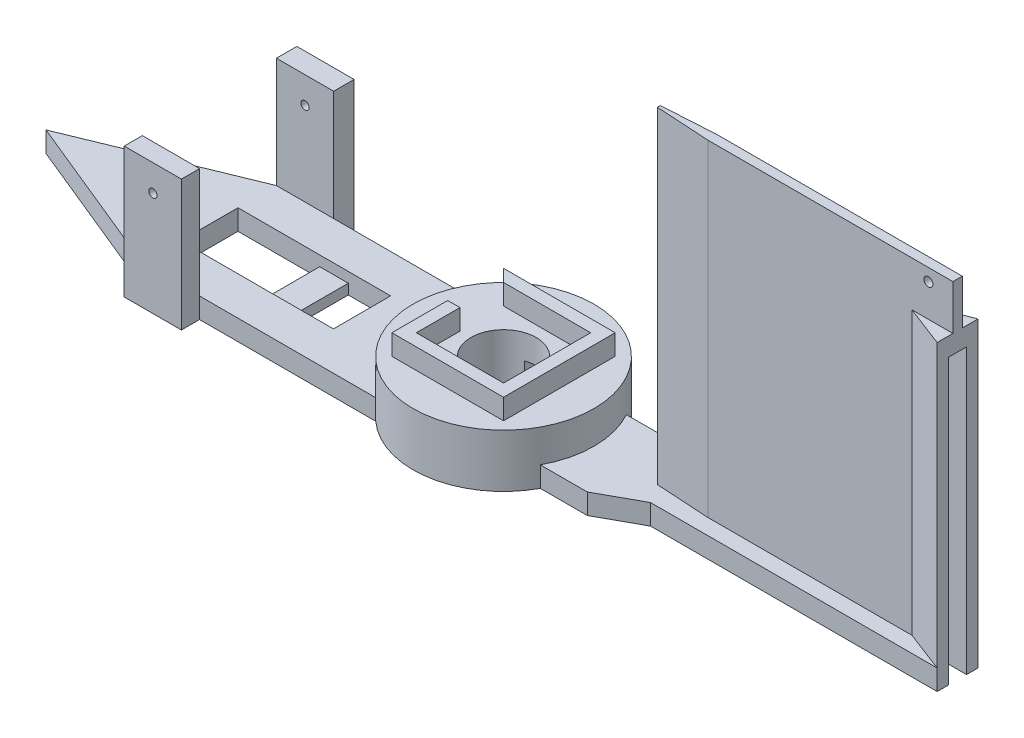
SolidWorks part; units mm, degrees
ref_plane "Front Plane" through (0, 0, 0) normal (0, 0, 1) x (1, 0, 0)
ref_plane "Top Plane" through (0, 0, 0) normal (0, 1, 0) x (1, 0, 0)
ref_plane "Right Plane" through (0, 0, 0) normal (1, 0, 0) x (0, 0, -1)
sketch "Sketch1" plane through (0, 0, 0) normal (0, 1, 0) x (1, 0, 0)
  circle A0 centre (0, 0) radius 16.15
  circle A1 centre (0, 0) radius 22.15
  dimension "D1" = 32.3
  dimension "D2" = 44.3
extrude "Boss-Extrude1" add sketch "Sketch1" along normal blind 10
sketch "Sketch2" plane through (0, 10, 0) normal (0, 1, 0) x (1, 0, 0)
  circle A0 centre (0, 0) radius 22.15
  circle A1 centre (0, 0) radius 12.15
  dimension "D1" = 24.3
extrude "Boss-Extrude2" add sketch "Sketch2" along normal blind 3
sketch "Sketch3" plane through (0, 13, 0) normal (0, 1, 0) x (1, 0, 0)
  line L0 (0, 0) -> (-65, 0)
  line L1 (-65, 0) -> (-65, -16.41)
  line L2 (-65, 0) -> (-65, 16.41)
  line L3 (-65, -16.41) -> (0, -16.41)
  line L4 (0, -16.41) -> (0, 0)
  line L5 (-65, 16.41) -> (0, 16.41)
  line L6 (0, 16.41) -> (0, 0)
  circle A0 centre (0, 0) radius 22.15
  circle M4 centre (0, 0) radius 22.15
  dimension "D1" = 65
  dimension "D2" = 16.41
extrude "Boss-Extrude3" add sketch "Sketch3" against normal up to surface (5 mm away) from offset 8 contours L5 L2 L0 M4 | L1 L3 L0 M4 up to face at (0, 0, 22.15) offset against normal yes
sketch "Sketch10" plane through (0, 5, 0) normal (0, 1, 0) x (1, 0, 0)
  line L1 (-65, -16.41) -> (-58, -16.41)
  line L2 (-65, -16.41) -> (-65, -20.8481)
  line L3 (-65, -20.8481) -> (-58, -20.8481)
  line L4 (-58, -16.41) -> (-58, -20.8481)
  line L5 (-65, -16.41) -> (-72, -16.41)
  line L6 (-65, -16.41) -> (-65, -20.8481)
  line L7 (-65, -20.8481) -> (-72, -20.8481)
  line L8 (-72, -16.41) -> (-72, -20.8481)
  line L9 (-65, 16.41) -> (-58, 16.41)
  line L10 (-65, 16.41) -> (-65, 21.41)
  line L11 (-65, 21.41) -> (-58, 21.41)
  line L12 (-58, 16.41) -> (-58, 21.41)
  line L13 (-65, 16.41) -> (-72, 16.41)
  line L14 (-65, 16.41) -> (-65, 21.41)
  line L15 (-65, 21.41) -> (-72, 21.41)
  line L16 (-72, 16.41) -> (-72, 21.41)
  line M6 (-14.8773, 16.41) -> (-65, 16.41)
  line M8 (-65, -16.41) -> (-14.8773, -16.41)
  dimension "D1" = 7
  dimension "D2" = 5
extrude "Boss-Extrude5" add sketch "Sketch10" along normal blind 27 separate body contours L5 L8 L7 L2 | L4 L2 L3 M8 | L16 L13 L10 L15 | L12 L11 L10 M6
sketch "Sketch11" plane through (0, 0, 20.8481) normal (0, 0, 1) x (1, 0, 0)
  line L0 (-65, 32) -> (-65, 25.5)
  line L1 (-58, 32) -> (-72, 32) construction
  circle A0 centre (-65, 25.5) radius 1
  dimension "D2" = 2
  dimension "D1" = 6.5
extrude "Cut-Extrude2" cut sketch "Sketch11" against normal through all
sketch "Sketch12" plane through (0, 0, 0) normal (0, -1, 0) x (1, 0, 0)
  line L1 (-72, 20.8481) -> (-58, 20.8481)
  line L2 (-72, 20.8481) -> (-72, -21.41)
  line L3 (-72, -21.41) -> (-58, -21.41)
  line L4 (-58, 20.8481) -> (-58, -21.41)
extrude "Boss-Extrude6" add sketch "Sketch12" against normal up to surface (5 mm away) up to face at (-65, 5, 18.6291)
sketch "Sketch13" plane through (0, 0, 0) normal (0, -1, 0) x (1, 0, 0)
  line L1 (16.15, 0) -> (111.15, 0)
  line L2 (16.15, 0) -> (16.15, 5)
  line L3 (16.15, 5) -> (111.15, 5)
  line L4 (111.15, 0) -> (111.15, 5)
  line L5 (16.15, 0) -> (111.15, 0)
  line L6 (16.15, 0) -> (16.15, -5)
  line L7 (16.15, -5) -> (111.15, -5)
  line L8 (111.15, 0) -> (111.15, -5)
  circle A0 centre (0, 0) radius 16.15 construction
  circle A1 centre (0, 0) radius 16.15 construction
  arc M11 (-14.8773, -16.41) -> (-14.8773, 16.41) centre (0, 0) ccw
  dimension "D1" = 5
  dimension "D2" = 95
extrude "Boss-Extrude7" add sketch "Sketch13" against normal blind 5 contours L8 L1 L7 M11 | L1 L4 L3 M11
sketch "Sketch14" plane through (0, 5, 0) normal (0, 1, 0) x (1, 0, 0)
  line L0 (22.15, 0) -> (32.15, 0)
  line L1 (111.15, 0) -> (111.15, 1.15)
  line L2 (111.15, -5) -> (111.15, 5) construction
  line L3 (111.15, 0) -> (111.15, -1.15)
  line L6 (111.15, 1.15) -> (51.15, 1.15)
  line L7 (111.15, -1.15) -> (51.15, -1.15)
  line L8 (32.15, 0) -> (51.15, 1.15)
  line L9 (51.15, -1.15) -> (32.15, 0)
  arc A0 (21.5783, -5) -> (21.5783, 5) centre (0, 0) ccw construction
  dimension "D1" = 10
  dimension "D2" = 1.15
  dimension "D3" = 60
extrude "Boss-Extrude8" add sketch "Sketch14" along normal blind 80
sketch "Sketch16" plane through (0, 13, 0) normal (0, 1, 0) x (1, 0, 0)
  line L0 (0, 0) -> (0, -10.64)
  line L1 (0, -10.64) -> (-10.64, -10.64)
  line L2 (-10.64, -10.64) -> (-10.64, -13.14)
  line L3 (-10.64, -10.64) -> (10.7, -10.64)
  line L4 (-10.64, -10.64) -> (-10.64, 10.7)
  line L5 (-10.64, 10.7) -> (10.7, 10.7)
  line L6 (10.7, -10.64) -> (10.7, 10.7)
  line L7 (-10.64, -13.14) -> (-13.14, -13.14)
  line L9 (-13.14, -13.14) -> (13.2, -13.14)
  line L10 (-13.14, -13.14) -> (-13.14, 13.2)
  line L11 (-13.14, 13.2) -> (13.2, 13.2)
  line L12 (13.2, -13.14) -> (13.2, 13.2)
  dimension "D1" = 10.64
  dimension "D2" = 21.34
  dimension "D3" = 2.5
  dimension "D4" = 26.34
extrude "Boss-Extrude9" add sketch "Sketch16" along normal blind 6
sketch "Sketch17" plane through (0, 19, 0) normal (0, 1, 0) x (1, 0, 0)
  line L0 (-13.14, -13.14) -> (-13.14, 13.2) construction
  line L1 (-13.14, 0.03) -> (-10.64, 0.03)
  line L2 (-13.14, 0.03) -> (-13.14, 10.7)
  line L3 (-13.14, 10.7) -> (-10.64, 10.7)
  line L4 (-10.64, 0.03) -> (-10.64, 10.7)
extrude "Cut-Extrude3" cut sketch "Sketch17" against normal up to surface (6 mm away) up to face at (0, 13, 22.15)
sketch "Sketch20" plane through (0, 5, 0) normal (0, 1, 0) x (1, 0, 0)
  line L0 (-72, 0) -> (-112, 0)
  line L1 (-72, -16.41) -> (-72, 16.41) construction
  line L2 (-112, 0) -> (-72, 16.41)
  line L3 (-112, 0) -> (-72, -16.41)
  line M3 (-72, 16.41) -> (-72, -16.41)
  dimension "D1" = 40
extrude "Boss-Extrude11" add sketch "Sketch20" against normal blind 5 contours L2 L0 M3 | L0 L3 M3
sketch "Sketch23" plane through (0, 10, 0) normal (0, -1, 0) x (1, 0, 0)
  circle A0 centre (0, 0) radius 12.15
  circle A1 centre (0, 0) radius 8
  dimension "D1" = 16
extrude "Boss-Extrude12" add sketch "Sketch23" against normal up to surface (1 mm away) from offset 2 up to face at (9.2062, 13, 9.1283) offset against normal yes
sketch "Sketch24" plane through (0, 5, 0) normal (0, 1, 0) x (1, 0, 0)
  line L0 (-72, -16.41) -> (-72, 16.41)
  line L2 (-72, 0) -> (-34.6356, 0)
  line L3 (-72, 0) -> (-72, 7)
  line L4 (-72, 7) -> (-34.6356, 7)
  line L5 (-34.6356, 0) -> (-34.6356, 7)
  line L6 (-72, 0) -> (-34.6356, 0)
  line L7 (-72, 0) -> (-72, -7)
  line L8 (-72, -7) -> (-34.6356, -7)
  line L9 (-34.6356, 0) -> (-34.6356, -7)
  dimension "D1" = 7
extrude "Cut-Extrude5" cut sketch "Sketch24" against normal blind 10 contours L2 L5 L4 L0 | L9 L2 L0 L8
sketch "Sketch25" plane through (0, 0, 1.15) normal (0, 0, 1) x (1, 0, 0)
  line L0 (105.15, 85) -> (105.15, 81.95)
  line L1 (111.15, 85) -> (99.15, 85)
  line L2 (111.15, 85) -> (111.15, 77.5)
  line L3 (111.15, 77.5) -> (99.15, 77.5)
  line L4 (99.15, 85) -> (99.15, 77.5)
  circle A0 centre (105.15, 81.95) radius 1.1
  dimension "D4" = 2.2
  dimension "D1" = 12
  dimension "D2" = 7.5
  dimension "D3" = 3.05
extrude "Cut-Extrude6" cut sketch "Sketch25" against normal blind 10
sketch "Sketch28" plane through (0, 85, 0) normal (0, 1, 0) x (1, 0, 0)
  line L0 (32.15, 0) -> (36.15, 0)
  line L1 (36.15, 0) -> (36.15, -0.2421)
  line L2 (51.15, -1.15) -> (32.15, 0) construction
  line L3 (36.15, -0.2421) -> (32.15, 0)
  line L4 (36.15, 0) -> (36.15, 0.2421)
  line L5 (32.15, 0) -> (51.15, 1.15) construction
  line L6 (36.15, 0.2421) -> (32.15, 0)
  line M2 (32.15, 0) -> (51.15, -1.15)
  line M6 (51.15, 1.15) -> (32.15, 0)
  dimension "D1" = 4
extrude "Cut-Extrude8" cut sketch "Sketch28" against normal up to surface (80 mm away) contours L0 L4 M6 | L1 L0 M2 up to face at (69.1976, 5, 0)
sketch "Sketch29" plane through (0, 0, 0) normal (0, -1, 0) x (1, 0, 0)
  line L0 (111.15, 0) -> (111.15, 2.2)
  line L1 (111.15, 5) -> (111.15, -5) construction
  line L2 (111.15, 2.2) -> (20.4358, 2.2)
  line L3 (111.15, 0) -> (111.15, -2.2)
  line L4 (111.15, -2.2) -> (20.4358, -2.2)
  line L5 (-20.5539, 0) -> (-34.6356, 0)
  line L6 (-34.6356, 7) -> (-34.6356, -7) construction
  line L7 (-34.6356, 0) -> (-34.6356, 2.2)
  line L8 (-34.6356, 2.2) -> (-20.4358, 2.2)
  line L9 (-34.6356, 0) -> (-34.6356, -2.2)
  line L10 (-34.6356, -2.2) -> (-20.4358, -2.2)
  circle A0 centre (0, 0) radius 17.7539
  circle A1 centre (0, 0) radius 20.5539
  line M18 (111.15, -5) -> (111.15, 5)
  line M23 (-34.6356, 7) -> (-34.6356, -7)
  dimension "D2" = 2.8
  dimension "D1" = 2.2
  dimension "D3" = 2.2
extrude "Cut-Extrude9" cut sketch "Sketch29" against normal blind 2.5 contours A1 L4 L2 M18 | A1 A0 | A1 L5 L10 M23 | A1 L8 L5 M23
sketch "Sketch30" plane through (0, 13, 0) normal (0, 1, 0) x (1, 0, 0)
  line L0 (0, 0) -> (-38.34, 0)
  line L1 (-38.34, 0) -> (-38.34, 10.67)
  line L2 (38, 10.67) -> (38, 13.67)
  line L3 (-38.34, 10.67) -> (38, 10.67)
  line L4 (-38.34, 10.67) -> (-38.34, -10.5)
  line L5 (-38.34, -10.5) -> (38, -10.5)
  line L6 (38, 10.67) -> (38, -10.5)
  line L7 (38, 13.67) -> (41, 13.67)
  line L8 (-38.34, -10.5) -> (-38.34, -13.5)
  line L9 (-38.34, -13.5) -> (-41.34, -13.5)
  line L10 (-41.34, 13.67) -> (-31.34, 13.67)
  line L11 (-41.34, -13.5) -> (41, -13.5)
  line L12 (-41.34, -13.5) -> (-41.34, 13.67)
  line L13 (-41.34, 13.67) -> (41, 13.67)
  line L14 (41, -13.5) -> (41, 13.67)
  line L15 (-31.34, 13.67) -> (-31.34, -13.5)
  line L16 (41, 13.67) -> (31, 13.67)
  line L17 (31, 13.67) -> (31, -13.5)
  dimension "D1" = 38.34
  dimension "D2" = 10.67
  dimension "D3" = 76.34
  dimension "D4" = 21.17
  dimension "D5" = 3
  dimension "D6" = 10
  dimension "D7" = 10
extrude "Boss-Extrude13" add sketch "Sketch30" against normal up to surface (13 mm away) contours L15 L10 L12 L9 L8 L4 L1 L3 | L15 L5 L8 L11 | L5 L17 L11 L14 L7 L2 L6 | L13 L17 L3 L2 up to face at (-16.667, 0, -0.0416)
sketch "Sketch31" plane through (0, 13, 0) normal (0, 1, 0) x (1, 0, 0)
  line L1 (-41.34, 7) -> (-38.34, 7)
  line L2 (-41.34, 7) -> (-41.34, -7)
  line L3 (-41.34, -7) -> (-38.34, -7)
  line L4 (-38.34, 7) -> (-38.34, -7)
extrude "Cut-Extrude10" cut sketch "Sketch31" against normal through all
sketch "Sketch33" plane through (0, 5, 0) normal (0, 1, 0) x (1, 0, 0)
  line L0 (38, 0.3541) -> (36.15, 0.2421)
  line L1 (36.15, 0.2421) -> (36.15, -0.2421)
  line L2 (36.15, -0.2421) -> (38, -0.3541)
  line L3 (38, -0.3541) -> (38, 0.3541)
extrude "Cut-Extrude11" cut sketch "Sketch33" along normal through all
sketch "Sketch36" plane through (0, 19, 0) normal (0, 1, 0) x (1, 0, 0)
  line L1 (-13.14, 13.2) -> (13.2, 13.2)
  line L2 (-13.14, 13.2) -> (-13.14, -13.14)
  line L3 (-13.14, -13.14) -> (13.2, -13.14)
  line L4 (13.2, 13.2) -> (13.2, -13.14)
extrude "Cut-Extrude12" cut sketch "Sketch36" against normal up to surface (6 mm away) up to face at (-2.604, 13, -0.03)
sketch "Sketch37" plane through (0, 0, 0) normal (0, -1, 0) x (1, 0, 0)
  line L1 (38, 2.2) -> (41, 2.2)
  line L2 (38, 2.2) -> (38, -2.2)
  line L3 (38, -2.2) -> (41, -2.2)
  line L4 (41, 2.2) -> (41, -2.2)
extrude "Cut-Extrude13" cut sketch "Sketch37" against normal up to surface (2.5 mm away) up to face at (0, 2.5, -17.7539)
sketch "Sketch40" plane through (0, 5, 0) normal (0, 1, 0) x (1, 0, 0)
  line L0 (111.15, 5) -> (111.15, 1.15)
  line L1 (111.15, 1.15) -> (101.15, 1.15)
  line L2 (111.15, 1.15) -> (51.15, 1.15) construction
  line L3 (101.15, 1.15) -> (111.15, 5)
  line L4 (111.15, -5) -> (111.15, -1.15)
  line L5 (111.15, -1.15) -> (101.15, -1.15)
  line L6 (111.15, -1.15) -> (51.15, -1.15) construction
  line L7 (101.15, -1.15) -> (111.15, -5)
  line M6 (111.15, -5) -> (111.15, -1.15)
  line M7 (111.15, -1.15) -> (51.15, -1.15)
  dimension "D1" = 10
extrude "Boss-Extrude15" add sketch "Sketch40" along normal offset from surface (69 mm away) 11 contours L7 M7 M6 | L3 L1 L0 up to face at (66.7667, 85, 0)
sketch "Sketch41" plane through (111.15, 0, 0) normal (1, 0, 0) x (0, 0, -1)
  line L0 (-2.2, 2.5) -> (-2.2, 69.5)
  line L1 (-2.2, 69.5) -> (2.2, 69.5)
  line L2 (2.2, 69.5) -> (2.2, 2.5)
  line L3 (2.2, 2.5) -> (-2.2, 2.5)
  dimension "D1" = 67
extrude "Cut-Extrude14" cut sketch "Sketch41" against normal blind 5
sketch "Sketch42" plane through (38, 0, 0) normal (-1, 0, 0) x (0, 0, 1)
  line L1 (-10.67, 0) -> (-5, 0)
  line L2 (-10.67, 0) -> (-10.67, 5)
  line L3 (-10.67, 5) -> (-5, 5)
  line L4 (-5, 0) -> (-5, 5)
  line L5 (10.5, 0) -> (5, 0)
  line L6 (10.5, 0) -> (10.5, 5)
  line L7 (10.5, 5) -> (5, 5)
  line L8 (5, 0) -> (5, 5)
extrude "Boss-Extrude16" add sketch "Sketch42" along normal up to surface (18.5893 mm away)
sketch "Sketch43" plane through (0, 0, -7) normal (0, 0, 1) x (1, 0, 0)
  line L0 (-72, 0) -> (-34.6356, 0) construction
  line L1 (-52, 0) -> (-45, 0)
  line L2 (-52, 0) -> (-52, 5)
  line L3 (-52, 5) -> (-45, 5)
  line L4 (-45, 0) -> (-45, 5)
  line L5 (-72, 5) -> (-41.34, 5) construction
  line L6 (-72, 0) -> (-52, 0)
  line L7 (-52, 2.5) -> (-45, 2.5)
  line L8 (-52, 2.5) -> (-52, 0)
  line L9 (-52, 0) -> (-45, 0)
  line L10 (-45, 2.5) -> (-45, 0)
  line M8 (-72, 0) -> (-34.6356, 0)
  dimension "D1" = 7
  dimension "D2" = 20
extrude "Boss-Extrude17" add sketch "Sketch43" along normal up to surface (14 mm away) contours L7 L2 L4 M8 up to face at (-46.5789, 5.75, 7)
sketch "Sketch44" plane through (0, 13, 0) normal (0, 1, 0) x (1, 0, 0)
  line L0 (41, -0.5357) -> (38, -0.3541)
  line L1 (-41.34, 13.67) -> (-31.34, 13.67)
  line L2 (-41.34, 13.67) -> (-41.34, -13.5)
  line L3 (-41.34, -13.5) -> (-31.34, -13.5)
  line L4 (-31.34, 13.67) -> (-31.34, -13.5)
  line L5 (31, 13.67) -> (41, 13.67)
  line L6 (31, 13.67) -> (31, -13.5)
  line L7 (31, -13.5) -> (41, -13.5)
  line L8 (41, 13.67) -> (41, -13.5)
  line L9 (38, -0.3541) -> (38, 0.3541)
  line L10 (38, 0.3541) -> (41, 0.5357)
  line M1 (-41.34, 7) -> (-38.34, 7)
  line M2 (-38.34, 7) -> (-38.34, 10.67)
  line M3 (-38.34, 10.67) -> (-31.34, 10.67)
  line M4 (-31.34, 10.67) -> (-31.34, 13.67)
  line M5 (-31.34, 13.67) -> (-41.34, 13.67)
  line M6 (-41.34, 13.67) -> (-41.34, 7)
extrude "Cut-Extrude15" cut sketch "Sketch44" against normal up to surface (8 mm away) contours L9 L10 L8 L5 L6 L7 L0 | M6 M1 M2 M3 M4 M5 | L4 L2 L3 M3 M2 M1 up to face at (-58.4325, 5, 0)
sketch "Sketch45" plane through (0, 5, 0) normal (0, 1, 0) x (1, 0, 0)
  line L0 (31, -10.5) -> (41, -5)
  line L1 (41, -5) -> (41, -13.5)
  line L2 (41, -13.5) -> (31, -13.5)
  line L3 (31, -13.5) -> (31, -10.5)
  line L4 (31, 10.67) -> (41, 5)
  line L5 (41, 5) -> (41, 13.67)
  line L6 (41, 13.67) -> (31, 13.67)
  line L7 (31, 13.67) -> (31, 10.67)
  line M10 (31, -10.5) -> (31, -13.5)
  line M11 (31, -13.5) -> (41, -13.5)
  line M12 (41, -13.5) -> (41, -5)
extrude "Cut-Extrude16" cut sketch "Sketch45" against normal through all contours L0 M10 M11 M12 | L6 L7 L4 L5
sketch "Sketch48" plane through (0, 12, 0) normal (0, -1, 0) x (-1, 0, 0)
  circle A0 centre (0, 0) radius 12.15
  circle M1 centre (0, 0) radius 8
  circle M2 centre (0, 0) radius 12.15
extrude "Boss-Extrude18" add sketch "Sketch48" along normal up to surface (2 mm away) contours M2 M1 up to face at (0, 10, 12.15)
sketch "Sketch49" plane through (0, 10, 0) normal (0, -1, 0) x (1, 0, 0)
  circle A0 centre (0, 0) radius 16.15
  circle A1 centre (0, 0) radius 8
  circle M1 centre (0, 0) radius 16.15
  circle M2 centre (0, 0) radius 8
extrude "Boss-Extrude19" add sketch "Sketch49" along normal up to surface (10 mm away) contours M1 M2 up to face at (-62, 0, 0)
sketch "Sketch50" plane through (0, 0, 0) normal (0, -1, 0) x (-1, 0, 0)
  circle A0 centre (0, 0) radius 14.5
  circle A1 centre (0, 0) radius 17.7539
  dimension "D1" = 29
extrude "Cut-Extrude17" cut sketch "Sketch50" against normal up to surface (2.5 mm away) up to face at (17.8786, 2.5, 0)
sketch "Sketch51" plane through (0, 0, 0) normal (0, -1, 0) x (1, 0, 0)
  line L0 (0, 8) -> (0, -8)
  line L1 (-2.5, 5.5) -> (-2.5, -5.5)
  line L2 (-2.5, 5.5) -> (2.5, 5.5)
  line L3 (-2.5, 5.5) -> (-2.5, 10.5)
  line L4 (-2.5, 10.5) -> (2.5, 10.5)
  line L5 (2.5, 5.5) -> (2.5, 10.5)
  line L6 (-2.5, 5.5) -> (2.5, 10.5) construction
  line L7 (-2.5, 10.5) -> (2.5, 5.5) construction
  line L8 (-2.5, -5.5) -> (2.5, -5.5)
  line L9 (-2.5, -5.5) -> (-2.5, -10.5)
  line L10 (-2.5, -10.5) -> (2.5, -10.5)
  line L11 (2.5, -5.5) -> (2.5, -10.5)
  line L12 (-2.5, -5.5) -> (2.5, -10.5) construction
  line L13 (-2.5, -10.5) -> (2.5, -5.5) construction
  circle A0 centre (0, 0) radius 8 construction
  circle M5 centre (0, 0) radius 8
  dimension "D1" = 5
extrude "Cut-Extrude18" cut sketch "Sketch51" against normal blind 7 contours L5 L4 L3 M5 | L11 L9 L10 M5
sketch "Sketch52" plane through (0, 13, 0) normal (0, 1, 0) x (1, 0, 0)
  line L0 (-10.67, 0) -> (-13.67, 0)
  line L1 (10.67, -10.67) -> (-10.67, -10.67)
  line L2 (10.67, -10.67) -> (10.67, 10.67)
  line L3 (10.67, 10.67) -> (-10.67, 10.67)
  line L4 (-10.67, -10.67) -> (-10.67, 10.67)
  line L5 (10.67, -10.67) -> (-10.67, 10.67) construction
  line L6 (10.67, 10.67) -> (-10.67, -10.67) construction
  line L7 (-13.67, -13.67) -> (13.67, -13.67)
  line L8 (-13.67, -13.67) -> (-13.67, 13.67)
  line L9 (-13.67, 13.67) -> (13.67, 13.67)
  line L10 (13.67, -13.67) -> (13.67, 13.67)
  line L11 (-13.67, -13.67) -> (13.67, 13.67) construction
  line L12 (-13.67, 13.67) -> (13.67, -13.67) construction
  line L13 (-10.67, 10.67) -> (-13.67, 13.67)
  point P0 (0, 0)
  point P6 (0, 0)
  dimension "D1" = 21.34
  dimension "D2" = 27.34
extrude "Boss-Extrude20" add sketch "Sketch52" along normal blind 5 contours L13 L3 L2 L1 L4 L0 L8 L7 L10 L9
sketch "Sketch53" plane through (0, 0, 0) normal (0, -1, 0) x (1, 0, 0)
  line L1 (-20.4358, 2.2) -> (20.4358, 2.2)
  line L2 (-20.4358, 2.2) -> (-20.4358, -2.2)
  line L3 (-20.4358, -2.2) -> (20.4358, -2.2)
  line L4 (20.4358, 2.2) -> (20.4358, -2.2)
  circle M5 centre (0, 0) radius 14.5
  arc M13 (-2.5, -7.5993) -> (-2.5, 7.5993) centre (0, 0) cw
extrude "Cut-Extrude20" cut sketch "Sketch53" against normal up to surface (2.5 mm away) contours L3 L1 M5 M13
